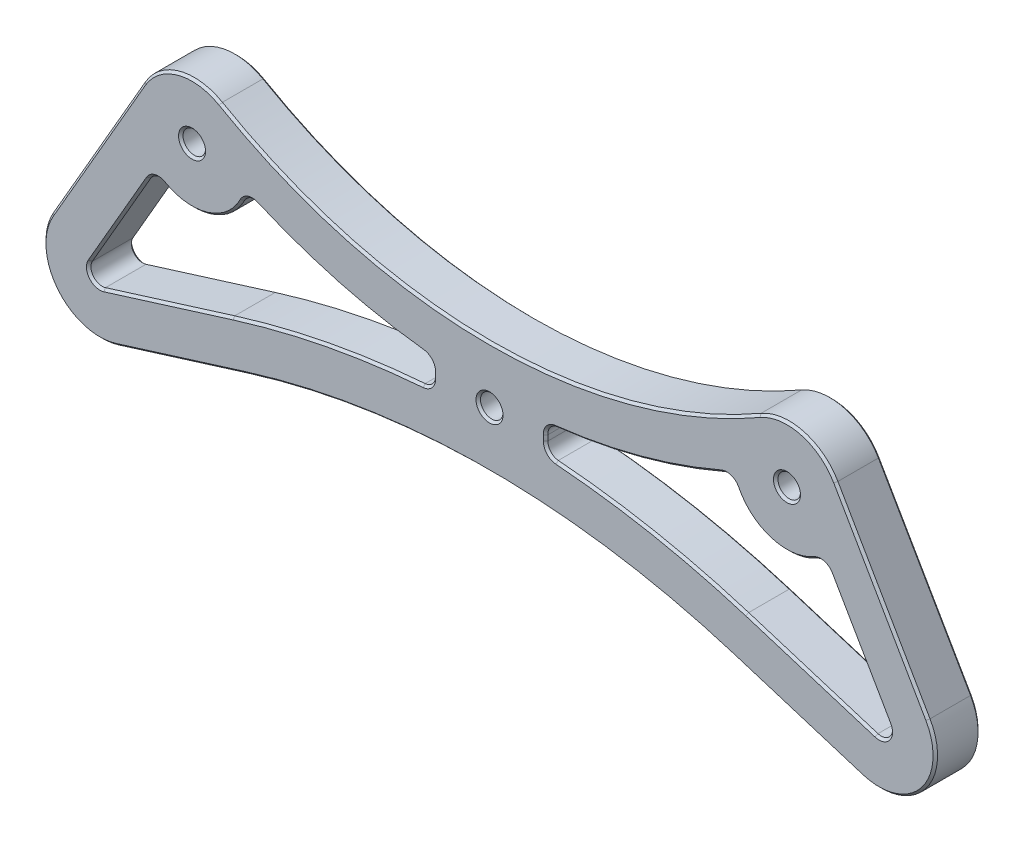
SolidWorks part; units mm, degrees
ref_plane "Front Plane" through (0, 0, 0) normal (0, 0, 1) x (1, 0, 0)
ref_plane "Top Plane" through (0, 0, 0) normal (0, 1, 0) x (1, 0, 0)
ref_plane "Right Plane" through (0, 0, 0) normal (1, 0, 0) x (0, 0, -1)
sketch "Sketch1" plane through (0, 0, 0) normal (0, 0, 1) x (1, 0, 0)
  line L0 (0, 0) -> (-95.2628, -55) construction
  line L1 (0, 0) -> (0, -110) construction
  line L2 (0, 0) -> (-55, -95.2628) construction
  line L3 (-55, -95.2628) -> (-74.282, -128.6603) construction
  line L4 (-66.3088, -129.5478) -> (-43.3201, -122.389)
  line L5 (-77.9423, -115) -> (-61.5603, -86.6255)
  line L6 (0, 0) -> (-52.9, -91.6255) construction
  line L7 (0, 0) -> (0, -105.8) construction
  line L8 (-69.282, -130) -> (0, -130) construction
  line L9 (0, -110) -> (0, -261.5011) construction
  line L10 (-52.9, -91.6255) -> (-61.5603, -86.6255) construction
  line L11 (0, -261.5011) -> (-52.9, -91.6255) construction
  line L12 (77.9423, -115) -> (61.5603, -86.6255)
  line L13 (66.3088, -129.5478) -> (43.3201, -122.389)
  line L14 (-77.9423, -115) -> (-69.282, -120) construction
  line L15 (-66.3088, -129.5478) -> (-69.282, -120) construction
  line L16 (-71.0141, -119) -> (-60.6321, -101.0178)
  line L19 (-68.6874, -121.9096) -> (-45.6987, -114.7508)
  line L20 (71.0141, -119) -> (60.6321, -101.0178)
  line L21 (68.6874, -121.9096) -> (45.6987, -114.7508)
  circle A0 centre (0, 0) radius 110 construction
  circle A1 centre (-52.9, -91.6255) radius 2
  arc A2 (-77.9423, -115) -> (-66.3088, -129.5478) centre (-69.282, -120) ccw
  circle A3 centre (0, -105.8) radius 2
  circle A4 centre (52.9, -91.6255) radius 2
  arc A5 (-43.3201, -122.389) -> (43.3201, -122.389) centre (0, -261.5011) cw
  arc A6 (-61.5603, -86.6255) -> (-47.9, -82.9652) centre (-52.9, -91.6255) cw
  arc A7 (-47.9, -82.9652) -> (47.9, -82.9652) centre (0, 0) ccw
  arc A8 (61.5603, -86.6255) -> (47.9, -82.9652) centre (52.9, -91.6255) ccw
  arc A9 (77.9423, -115) -> (66.3088, -129.5478) centre (69.282, -120) cw
  arc A11 (-71.0141, -119) -> (-68.6874, -121.9096) centre (-69.282, -120) ccw
  arc A14 (-45.6987, -114.7508) -> (-11.8371, -108.2565) centre (0, -261.5011) cw
  arc A15 (-11.7542, -103.1323) -> (-41.3867, -95.1923) centre (0, 0) cw
  arc A16 (-57.9, -100.2857) -> (-43.9701, -96.1263) centre (-52.9, -91.6255) ccw
  arc A18 (-9.9839, -105.2329) -> (-9.9926, -106.1854) centre (0, -105.8) ccw
  arc A19 (-11.8371, -108.2565) -> (-9.9926, -106.1854) centre (-11.9911, -106.2624) ccw
  arc A20 (-9.9839, -105.2329) -> (-11.7542, -103.1323) centre (-11.9807, -105.1195) ccw
  arc A21 (-41.3867, -95.1923) -> (-43.9701, -96.1263) centre (-42.1842, -97.0265) ccw
  arc A22 (-60.6321, -101.0178) -> (-57.9, -100.2857) centre (-58.9, -102.0178) cw
  arc A23 (45.6987, -114.7508) -> (11.8371, -108.2565) centre (0, -261.5011) ccw
  arc A24 (11.8371, -108.2565) -> (9.9926, -106.1854) centre (11.9911, -106.2624) cw
  arc A25 (9.9839, -105.2329) -> (9.9926, -106.1854) centre (0, -105.8) cw
  arc A26 (9.9839, -105.2329) -> (11.7542, -103.1323) centre (11.9807, -105.1195) cw
  arc A27 (11.7542, -103.1323) -> (41.3867, -95.1923) centre (0, 0) ccw
  arc A28 (41.3867, -95.1923) -> (43.9701, -96.1263) centre (42.1842, -97.0265) cw
  arc A29 (57.9, -100.2857) -> (43.9701, -96.1263) centre (52.9, -91.6255) cw
  arc A30 (60.6321, -101.0178) -> (57.9, -100.2857) centre (58.9, -102.0178) ccw
  arc A31 (71.0141, -119) -> (68.6874, -121.9096) centre (69.282, -120) cw
  point P31 (0, -115.8)
  dimension "D1" = 220
  dimension "D4" = 4
  dimension "D6" = 10
  dimension "D10" = 2
  dimension "D12" = 2
  dimension "D2" = 60
  dimension "D5" = 105.8
  dimension "D8" = 30
  dimension "D9" = 20
  dimension "D3" = 10
  dimension "D11" = 8
  dimension "D7" = 3
extrude "Boss-Extrude1" add sketch "Sketch1" along normal blind 8
chamfer "Chamfer1" distance 0.4 angle 45 70 edges at (10.4975, -107.5926, 0) (9.9996, -105.709, 0) (10.4514, -103.8306, 0) (26.8654, -100.2631, 0) (42.8641, -95.1456, 0) (50.0388, -101.2074, 0) (59.4176, -100.0859, 0) (65.8231, -110.0089, 0) (70.844, -121.2491, 0) (57.193, -118.3302, 0) (28.9506, -110.5511, 0) (54.9, -91.6255, 0) (2, -105.8, 0) (-50.9, -91.6255, 0) (-54.8145, -125.9684, 0) (0, -115.8, 0) (54.8145, -125.9684, 0) (77.092, -126.2454, 0) (69.7513, -100.8127, 0) (55.4882, -81.9662, 0) (0, -95.8, 0) (-55.4882, -81.9662, 0) (-69.7513, -100.8127, 0) (-77.092, -126.2454, 0) (-65.8231, -110.0089, 0) (-59.4176, -100.0859, 0) (-50.0388, -101.2074, 0) (-42.8641, -95.1456, 0) (-26.8654, -100.2631, 0) (-10.4514, -103.8306, 0) (-9.9996, -105.709, 0) (-10.4975, -107.5926, 0) (-28.9506, -110.5511, 0) (-57.193, -118.3302, 0) (-70.844, -121.2491, 0) (70.844, -121.2491, 8) (65.8231, -110.0089, 8) (59.4176, -100.0859, 8) (50.0388, -101.2074, 8) (42.8641, -95.1456, 8) (26.8654, -100.2631, 8) (10.4514, -103.8306, 8) (9.9996, -105.709, 8) (10.4975, -107.5926, 8) (28.9506, -110.5511, 8) (57.193, -118.3302, 8) (-28.9506, -110.5511, 8) (-10.4975, -107.5926, 8) (-9.9996, -105.709, 8) (-10.4514, -103.8306, 8) (-26.8654, -100.2631, 8) (-42.8641, -95.1456, 8) (-50.0388, -101.2074, 8) (-59.4176, -100.0859, 8) (-65.8231, -110.0089, 8) (-70.844, -121.2491, 8) (-57.193, -118.3302, 8) (54.9, -91.6255, 8) (-50.9, -91.6255, 8) (-69.7513, -100.8127, 8) (-55.4882, -81.9662, 8) (0, -95.8, 8) (55.4882, -81.9662, 8) (69.7513, -100.8127, 8) (77.092, -126.2454, 8) (54.8145, -125.9684, 8) (0, -115.8, 8) (-54.8145, -125.9684, 8) (-77.092, -126.2454, 8) (2, -105.8, 8)
equation "\"D11@Sketch1\"=\"D6@Sketch1\"-\"D10@Sketch1\""
